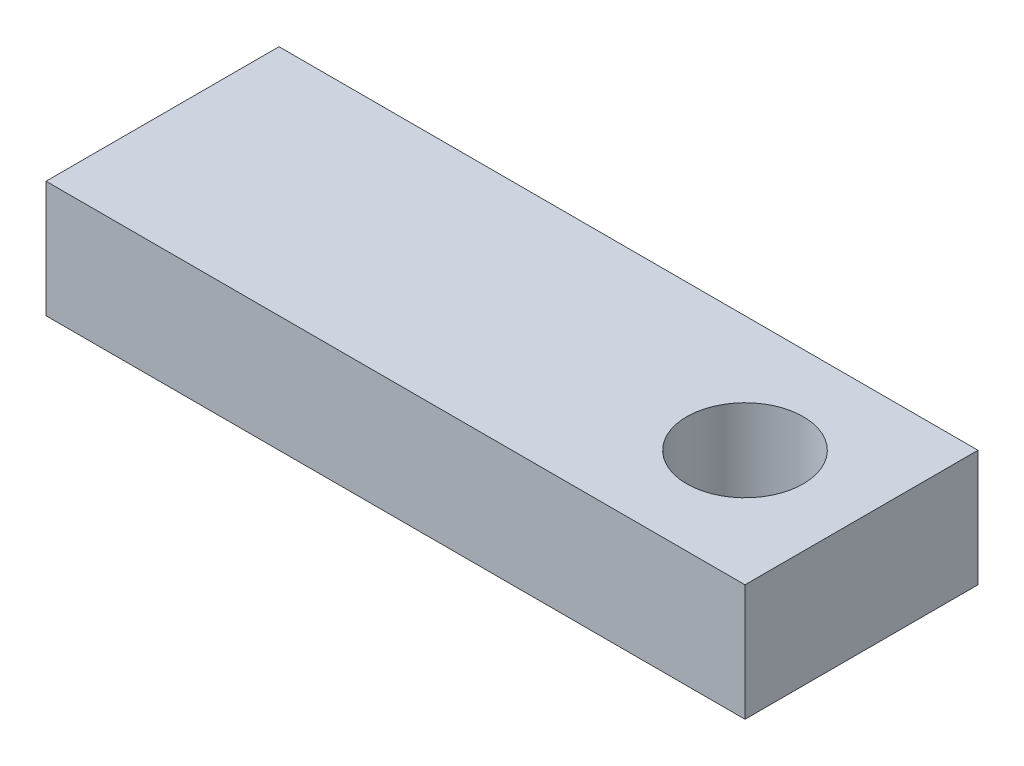
SolidWorks part; units mm, degrees
ref_plane "Front Plane" through (0, 0, 0) normal (0, 0, 1) x (1, 0, 0)
ref_plane "Top Plane" through (0, 0, 0) normal (0, 1, 0) x (1, 0, 0)
ref_plane "Right Plane" through (0, 0, 0) normal (1, 0, 0) x (0, 0, -1)
sketch "Sketch1" plane through (0, 0, 0) normal (0, 1, 0) x (1, 0, 0)
  line L0 (31.75, 0) -> (38.1, 0) construction
  line L1 (-38.1, -12.7) -> (38.1, -12.7)
  line L2 (-38.1, -12.7) -> (-38.1, 12.7)
  line L3 (-38.1, 12.7) -> (38.1, 12.7)
  line L4 (38.1, -12.7) -> (38.1, 12.7)
  line L5 (0, 12.7) -> (0, -12.7) construction
  line L6 (-38.1, 0) -> (19.05, 0) construction
  circle A0 centre (25.4, 0) radius 6.35
  point P0 (0, 0)
  dimension "D3" = 12.7
  dimension "D1" = 76.2
  dimension "D2" = 25.4
extrude "Boss-Extrude1" add sketch "Sketch1" along normal blind 12.7 contours L1 L4 L3 L2 A0
